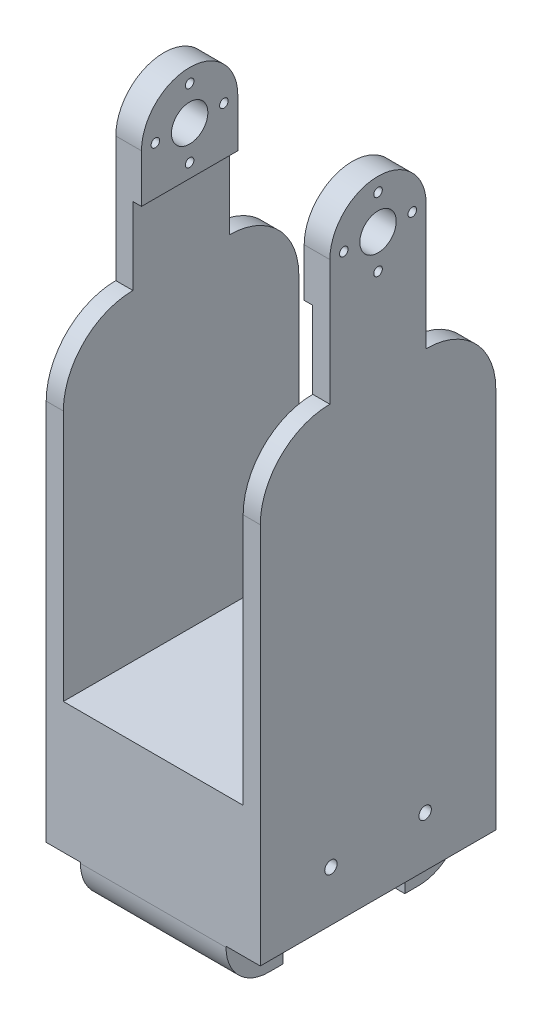
SolidWorks part; units mm, degrees
ref_plane "Front Plane" through (0, 0, 0) normal (0, 0, 1) x (1, 0, 0)
ref_plane "Top Plane" through (0, 0, 0) normal (0, 1, 0) x (1, 0, 0)
ref_plane "Right Plane" through (0, 0, 0) normal (1, 0, 0) x (0, 0, -1)
sketch "Sketch1" plane through (0, 0, 0) normal (0, 0, 1) x (1, 0, 0)
  line L1 (-25, 0) -> (25, 0)
  line L2 (-25, 0) -> (-25, -170)
  line L3 (-25, -170) -> (25, -170)
  line L4 (25, 0) -> (25, -170)
  dimension "D1" = 170
  dimension "D2" = 50
extrude "Boss-Extrude1" add sketch "Sketch1" against normal blind 55
sketch "Sketch2" plane through (0, 0, 0) normal (0, 0, 1) x (1, 0, 0)
  line L0 (25, 0) -> (-25, 0) construction
  line L1 (-17, 0) -> (17, 0)
  line L2 (-17, 0) -> (-17, -27)
  line L3 (-17, -27) -> (17, -27)
  line L4 (17, 0) -> (17, -27)
  line L5 (-25, 0) -> (-25, -170) construction
  dimension "D1" = 8
  dimension "D2" = 34
  dimension "D3" = 27
extrude "Cut-Extrude1" cut sketch "Sketch2" against normal through all
sketch "Sketch3" plane through (25, 0, 0) normal (1, 0, 0) x (0, 0, -1)
  line L0 (0, -170) -> (0, 0) construction
  line L1 (55, -27) -> (0, -27)
  line L2 (55, -27) -> (55, -24)
  line L3 (55, -24) -> (0, -24)
  line L4 (0, -27) -> (0, -24)
  line L5 (55, -170) -> (55, 0) construction
  line L7 (0, 0) -> (10, 0)
  line L8 (0, 0) -> (0, -24)
  line L9 (0, -24) -> (10, -24)
  line L10 (10, 0) -> (10, -24)
  line L11 (55, 0) -> (45, 0)
  line L12 (55, 0) -> (55, -24)
  line L13 (55, -24) -> (45, -24)
  line L14 (45, 0) -> (45, -24)
  circle A0 centre (27.5, -12.75) radius 10.25
  circle A1 centre (27.5, -12.75) radius 4.25
  circle A2 centre (27.5, -12.75) radius 8
  circle A3 centre (27.5, -4.75) radius 1
  circle A4 centre (35.5, -12.75) radius 1
  circle A5 centre (27.5, -20.75) radius 1
  circle A6 centre (19.5, -12.75) radius 1
  point P32 (27.5, -12.75)
  line M7 (0, 0) -> (0, -170)
  line M9 (55, -170) -> (55, 0)
  line M10 (55, 0) -> (0, 0)
  dimension "D2" = 11.25
  dimension "D3" = 27.5
  dimension "D4" = 20.5
  dimension "D7" = 8.5
  dimension "D8" = 16
  dimension "D9" = 4
  dimension "D1" = 3
  dimension "D5" = 10
  dimension "D6" = 10
extrude "Cut-Extrude2" cut sketch "Sketch3" against normal through all contours L14 L3 M10 M9 | L10 L3 M10 M7 | A2 A6 | A2 A6 | A1 | A2 A5 | A2 A5 | A2 A4 | A2 A4 | A2 A3 | A2 A3
sketch "Sketch4" plane through (0, 0, -10) normal (0, 0, 1) x (1, 0, 0)
  line L0 (-25, -24) -> (-17, -24) construction
  line L1 (-17, 0) -> (-19, 0)
  line L2 (-17, 0) -> (-17, -24)
  line L3 (-17, -24) -> (-19, -24)
  line L4 (-19, 0) -> (-19, -24)
  line L5 (0, 0) -> (0, -13.53) construction
  line L6 (19, 0) -> (19, -24)
  line L7 (17, -24) -> (19, -24)
  line L8 (17, 0) -> (17, -24)
  line L9 (17, 0) -> (19, 0)
  dimension "D1" = 2
extrude "Cut-Extrude3" cut sketch "Sketch4" against normal through all
sketch "Sketch5" plane through (25, 0, 0) normal (1, 0, 0) x (0, 0, -1)
  line L1 (10, 0) -> (45, 0)
  line L2 (10, 0) -> (10, -24)
  line L3 (10, -24) -> (45, -24)
  line L4 (45, 0) -> (45, -24)
  line L5 (38.75, -12.75) -> (38.75, -24)
  line L6 (16.25, -12.75) -> (10, -12.75)
  line L7 (16.25, -12.75) -> (16.25, -24)
  line L8 (16.25, -24) -> (10, -24)
  line L9 (10, -12.75) -> (10, -24)
  line L10 (38.75, -12.75) -> (45, -12.75)
  line L11 (38.75, -12.75) -> (38.75, -24)
  line L12 (38.75, -24) -> (45, -24)
  line L13 (45, -12.75) -> (45, -24)
  circle A0 centre (27.5, -12.75) radius 11.25
  line M8 (45, -24) -> (45, 0)
  line M9 (45, 0) -> (10, 0)
  line M10 (10, 0) -> (10, -24)
  dimension "D1" = 22.5
extrude "Cut-Extrude4" cut sketch "Sketch5" against normal through all contours A0 L10 L4 L6 M9 M10 | L7 L6 L2 L3 | L10 L5 L3 M8
sketch "Sketch6" plane through (0, 0, 0) normal (0, 0, 1) x (1, 0, 0)
  line L1 (-19, -24) -> (19, -24)
  line L2 (-19, -24) -> (-19, -34)
  line L3 (-19, -34) -> (19, -34)
  line L4 (19, -24) -> (19, -34)
  dimension "D1" = 10
extrude "Cut-Extrude5" cut sketch "Sketch6" against normal through all
sketch "Sketch8" plane through (25, 0, 0) normal (1, 0, 0) x (0, 0, -1)
  line L0 (55, -170) -> (55, -24) construction
  line L1 (0, -170) -> (0, -24) construction
  line L2 (41.75, -132.5) -> (13.25, -132.5)
  line L3 (27.5, -132.5) -> (27.5, -179)
  line L4 (41.75, -179) -> (13.25, -179)
  line L5 (13.25, -132.5) -> (13.25, -179)
  line L7 (41.75, -132.5) -> (41.75, -179)
  line L11 (27.5, -167.75) -> (55, -167.75)
  line L12 (27.5, -167.75) -> (27.5, -170)
  line L13 (27.5, -170) -> (55, -170)
  line L14 (55, -167.75) -> (55, -170)
  line L16 (27.5, -167.75) -> (0, -167.75)
  line L17 (27.5, -167.75) -> (27.5, -170)
  line L18 (27.5, -170) -> (0, -170)
  line L19 (0, -167.75) -> (0, -170)
  circle A0 centre (27.5, -167.75) radius 10.25
  circle A1 centre (27.5, -12.75) radius 10.25
  line M4 (0, -24) -> (0, -170)
  line M5 (0, -170) -> (55, -170)
  line M6 (55, -170) -> (55, -24)
  dimension "D1" = 27.5
  dimension "D2" = 20.5
  dimension "D3" = 155
  dimension "D4" = 14.25
  dimension "D5" = 11.25
  dimension "D6" = 46.5
  dimension "D7" = 13.25
extrude "Cut-Extrude7" cut sketch "Sketch8" against normal through all contours A0 L3 L2 L5 L16 | A0 L11 L7 L2 L3 | L11 L7 M5 M6 | L5 L16 M4 M5 | A0 L16 L5 M5 | A0 L13 L7 L11 | L3 A0 L16 | L11 A0 L3 | L16 A0 L18 L3 | A0 L11 L3 M5
sketch "Sketch9" plane through (0, 0, 0) normal (0, 0, 1) x (1, 0, 0)
  line L0 (-25, -167.75) -> (25, -167.75) construction
  line L1 (17, -167.75) -> (-17, -167.75)
  line L2 (17, -167.75) -> (17, -132.5)
  line L3 (17, -132.5) -> (-17, -132.5)
  line L4 (-17, -167.75) -> (-17, -132.5)
  line L5 (-25, -132.5) -> (25, -132.5) construction
  line L7 (-25, -24) -> (-25, -167.75) construction
  line L9 (25, -167.75) -> (25, -24) construction
  dimension "D1" = 8
  dimension "D2" = 8
extrude "Cut-Extrude8" cut sketch "Sketch9" against normal through all
sketch "Sketch11" plane through (25, 0, 0) normal (1, 0, 0) x (0, 0, -1)
  line L0 (27.5, -157.5) -> (27.5, -147.5)
  line L2 (27.5, -147.5) -> (55, -147.5)
  line L3 (27.5, -147.5) -> (27.5, -167.75)
  line L4 (27.5, -167.75) -> (55, -167.75)
  line L5 (55, -147.5) -> (55, -167.75)
  line L6 (27.5, -147.5) -> (0, -147.5)
  line L7 (27.5, -147.5) -> (27.5, -167.75)
  line L8 (27.5, -167.75) -> (0, -167.75)
  line L9 (0, -147.5) -> (0, -167.75)
  circle A0 centre (27.5, -167.75) radius 10.25
  arc A1 (38.75, -12.75) -> (16.25, -12.75) centre (27.5, -12.75) ccw construction
  line M1 (0, -167.75) -> (13.25, -167.75)
  line M2 (13.25, -167.75) -> (13.25, -132.5)
  line M4 (41.75, -132.5) -> (41.75, -167.75)
  line M5 (41.75, -167.75) -> (55, -167.75)
  line M6 (55, -167.75) -> (55, -24)
  line M12 (0, -24) -> (0, -167.75)
  dimension "D1" = 155
  dimension "D2" = 20.5
  dimension "D3" = 10
extrude "Cut-Extrude9" cut sketch "Sketch11" against normal through all contours A0 L0 L6 L8 M2 | A0 L4 L2 L0 M4 | L2 M4 M5 M6 | L6 M2 M12 M1
sketch "Sketch12" plane through (25, 0, 0) normal (1, 0, 0) x (0, 0, -1)
  line L1 (13.25, -132.5) -> (41.75, -132.5)
  line L2 (13.25, -132.5) -> (13.25, -147.5)
  line L3 (13.25, -147.5) -> (41.75, -147.5)
  line L4 (41.75, -132.5) -> (41.75, -147.5)
extrude "Boss-Extrude2" add sketch "Sketch12" against normal blind 8
ref_plane "Plane1" through (0, 0, 0) normal (1, 0, 0) x (0, 0, -1)
mirror "Mirror1" about plane through (0, 0, 0) normal (1, 0, 0) of "Boss-Extrude2"
sketch "Sketch14" plane through (0, 0, 0) normal (0, 0, 1) x (1, 0, 0)
  line L0 (17, -148.55) -> (17, -158.75) construction
  line L1 (-17, -132.5) -> (17, -132.5)
  line L2 (-17, -132.5) -> (-17, -147.5)
  line L3 (-17, -147.5) -> (17, -147.5)
  line L4 (17, -132.5) -> (17, -147.5)
  line L5 (-17, -147.5) -> (17, -147.5)
  line L6 (-17, -147.5) -> (-17, -157.75)
  line L7 (-17, -157.75) -> (17, -157.75)
  line L8 (17, -147.5) -> (17, -157.75)
  line M11 (-17, -147.5) -> (-17, -132.5)
  line M12 (-17, -132.5) -> (17, -132.5)
  line M13 (17, -132.5) -> (17, -147.5)
  dimension "D1" = 10.25
extrude "Boss-Extrude3" add sketch "Sketch14" against normal blind 13.25 contours L3 M11 M13 M12 | L8 L3 L6 L7
ref_plane "Plane2" through (0, 0, -27.5) normal (0, 0, 1) x (1, 0, 0)
mirror "Mirror2" about plane through (0, 0, -27.5) normal (0, 0, 1) of "Boss-Extrude3"
sketch "Sketch16" plane through (25, 0, 0) normal (1, 0, 0) x (0, 0, -1)
  line L0 (41.75, -132.5) -> (13.25, -132.5) construction
  line L1 (13.25, -132.5) -> (13.25, -147.5) construction
  circle A1 centre (16.5, -135.75) radius 2.5
  circle A2 centre (16.5, -135.75) radius 4.5
  circle A3 centre (38.5, -135.75) radius 4.5
  dimension "D1" = 3.25
  dimension "D2" = 3.25
  dimension "D3" = 2
extrude "Cut-Extrude13" cut sketch "Sketch16" against normal blind 8 contours A1 | A2 A1 | A3
mirror "Mirror3" about plane through (0, 0, 0) normal (1, 0, 0) of "Cut-Extrude13"
sketch "Sketch17" plane through (25, 0, 0) normal (1, 0, 0) x (0, 0, -1)
  line L0 (55, -147.5) -> (55, -24) construction
  line L1 (38.75, -24) -> (55, -24)
  line L2 (38.75, -24) -> (38.75, -42)
  line L3 (38.75, -42) -> (55, -42)
  line L4 (55, -24) -> (55, -42)
  line L5 (0, -147.5) -> (0, -24) construction
  line L6 (16.25, -24) -> (0, -24)
  line L7 (16.25, -24) -> (16.25, -42)
  line L8 (16.25, -42) -> (0, -42)
  line L9 (0, -24) -> (0, -42)
  dimension "D1" = 18
  dimension "D2" = 18
extrude "Cut-Extrude14" cut sketch "Sketch17" against normal through all
sketch "Sketch18" plane through (25, 0, 0) normal (1, 0, 0) x (0, 0, -1)
  line L9 (0, -147.5) -> (0, -42) construction
  line L18 (16.25, -42) -> (0, -42)
  line L19 (16.25, -42) -> (16.25, -58.25)
  line L20 (16.25, -58.25) -> (0, -58.25)
  line L21 (0, -42) -> (0, -58.25)
  line L22 (55, -147.5) -> (55, -42) construction
  line L23 (38.75, -42) -> (55, -42)
  line L24 (38.75, -42) -> (38.75, -58.25)
  line L25 (38.75, -58.25) -> (55, -58.25)
  line L26 (55, -42) -> (55, -58.25)
  circle A2 centre (16.25, -58.25) radius 16.25
  circle A3 centre (38.75, -58.25) radius 16.25
  line M9 (55, -42) -> (38.75, -42)
  line M13 (16.25, -42) -> (0, -42)
  line M14 (0, -42) -> (0, -147.5)
  line M16 (55, -147.5) -> (55, -42)
  dimension "D1" = 16.25
  dimension "D2" = 16.25
extrude "Cut-Extrude15" cut sketch "Sketch18" against normal through all contours A2 M13 M14 | A3 M16 M9
sketch "Sketch20" plane through (0, 0, -55) normal (0, 0, -1) x (-1, 0, 0)
  line L2 (21, -52) -> (21, -117)
  line L3 (21, -117) -> (-21, -117)
  line L4 (-21, -52) -> (-21, -117)
  line L5 (25, -58.25) -> (25, -147.5) construction
  line L6 (-25, -147.5) -> (-25, -58.25) construction
  line L7 (17, -157.75) -> (-17, -157.75) construction
  line L8 (21, -117) -> (-21, -117)
  line L9 (21, -117) -> (21, -52)
  line L10 (21, -52) -> (-21, -52)
  line L11 (-21, -117) -> (-21, -52)
  line L13 (21, -52) -> (-21, -52)
  line L14 (21, -52) -> (21, -34)
  line L15 (21, -34) -> (-21, -34)
  line L16 (-21, -52) -> (-21, -34)
  line M4 (25, -58.25) -> (-25, -58.25)
  dimension "D1" = 4
  dimension "D2" = 4
  dimension "D3" = 40.75
  dimension "D4" = 65
  dimension "D5" = 83
extrude "Cut-Extrude18" cut sketch "Sketch20" against normal through all contours L2 L10 L4 M4 | L16 L10 L14 L15 | L4 L3 L2 M4
sketch "Sketch22" plane through (-25, 0, 0) normal (-1, 0, 0) x (0, 0, 1)
  circle A0 centre (-38.5, -135.75) radius 4.5
  circle A1 centre (-38.5, -135.75) radius 1.45
  circle A2 centre (-16.5, -135.75) radius 4.5
  circle A3 centre (-16.5, -135.75) radius 1.45
  dimension "D1" = 2.9
extrude "Boss-Extrude4" add sketch "Sketch22" against normal blind 8
mirror "Mirror4" about plane through (0, 0, 0) normal (1, 0, 0) of "Boss-Extrude4"
sketch "Sketch23" plane through (0, 0, -38.75) normal (0, 0, -1) x (-1, 0, 0)
  line L0 (-19, -12.75) -> (-19, -34) construction
  line L1 (-21, -34) -> (-19, -34)
  line L2 (-21, -34) -> (-21, -24)
  line L3 (-21, -24) -> (-19, -24)
  line L4 (-19, -34) -> (-19, -24)
  line L5 (19, -34) -> (19, -12.75) construction
  line L6 (21, -34) -> (19, -34)
  line L7 (21, -34) -> (21, -24)
  line L8 (21, -24) -> (19, -24)
  line L9 (19, -34) -> (19, -24)
  dimension "D1" = 10
  dimension "D2" = 10
extrude "Cut-Extrude19" cut sketch "Sketch23" against normal through all
fillet "Fillet1" radius 10 2 edges at (0, -157.75, 0) (0, -157.75, -55)
